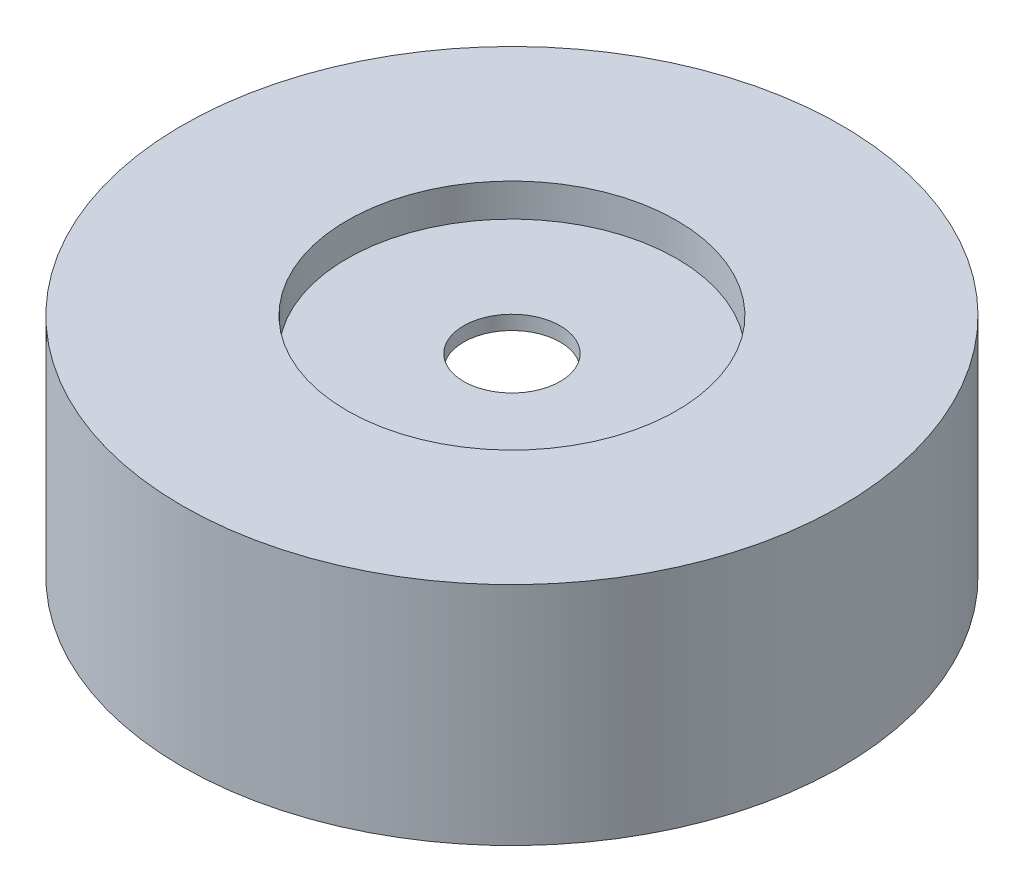
SolidWorks part; units mm, degrees
ref_plane "Front Plane" through (0, 0, 0) normal (0, 0, 1) x (1, 0, 0)
ref_plane "Top Plane" through (0, 0, 0) normal (0, 1, 0) x (1, 0, 0)
ref_plane "Right Plane" through (0, 0, 0) normal (1, 0, 0) x (0, 0, -1)
sketch "Sketch1" plane through (0, 0, 0) normal (0, 1, 0) x (1, 0, 0)
  circle A0 centre (0, 0) radius 70
  dimension "D1" = 140
extrude "Boss-Extrude1" add sketch "Sketch1" along normal blind 48
sketch "Sketch2" plane through (0, 48, 0) normal (0, 1, 0) x (1, 0, 0)
  circle A0 centre (0, 0) radius 35
  point P3 (1.6536, 0)
  point P4 (1.6536, 0)
  dimension "D1" = 70
  dimension "D2" = 0
  dimension "D3" = 0
extrude "Cut-Extrude1" cut sketch "Sketch2" against normal blind 7
sketch "Sketch3" plane through (0, 41, 0) normal (0, 1, 0) x (1, 0, 0)
  circle A0 centre (0, 0) radius 10.25
  dimension "D1" = 20.5
extrude "Cut-Extrude2" cut sketch "Sketch3" against normal through all
sketch "Sketch4" plane through (0, 0, 0) normal (0, -1, 0) x (1, 0, 0)
  circle A0 centre (0, 0) radius 65
  dimension "D1" = 130
extrude "Cut-Extrude4" cut sketch "Sketch4" against normal blind 38 contours A0
sketch "Sketch7" plane through (0, 38, 0) normal (0, -1, 0) x (1, 0, 0)
  line L0 (0, 0) -> (-50, 0)
  line L1 (-50, 0) -> (-65, 0)
  line L3 (-57.5, 4.9075) -> (-61.75, 2.4537)
  line L4 (-61.75, 2.4537) -> (-61.75, -2.4537)
  line L5 (-61.75, -2.4537) -> (-57.5, -4.9075)
  line L6 (-57.5, -4.9075) -> (-53.25, -2.4537)
  line L7 (-53.25, -2.4537) -> (-53.25, 2.4537)
  line L8 (-53.25, 2.4537) -> (-57.5, 4.9075)
  circle A0 centre (0, 0) radius 65 construction
  circle A1 centre (-57.5, 0) radius 4.25 construction
  dimension "D1" = 50
  dimension "D2" = 8.5
extrude "Boss-Extrude2" add sketch "Sketch7" along normal up to surface (38 mm away) contours L8 L3 L4 L5 L6 L7 up to face at (0, 0, -65)
sketch "Sketch10" plane through (0, 0, 0) normal (0, -1, 0) x (1, 0, 0)
  line L0 (-53.25, 0) -> (-61.75, 0) construction
  line L1 (-53.25, -2.4537) -> (-53.25, 2.4537) construction
  line L2 (-61.75, 2.4537) -> (-61.75, -2.4537) construction
  line L4 (-57.5, 3.1754) -> (-60.25, 1.5877)
  line L5 (-60.25, 1.5877) -> (-60.25, -1.5877)
  line L6 (-60.25, -1.5877) -> (-57.5, -3.1754)
  line L7 (-57.5, -3.1754) -> (-54.75, -1.5877)
  line L8 (-54.75, -1.5877) -> (-54.75, 1.5877)
  line L9 (-54.75, 1.5877) -> (-57.5, 3.1754)
  circle A0 centre (-57.5, 0) radius 2.75 construction
  dimension "D1" = 5.5
extrude "Cut-Extrude5" cut sketch "Sketch10" against normal blind 25 contours L9 L4 L5 L6 L7 L8
pattern_circular "CirPattern1" count 4 over 360 about axis through (0, 0, 0) along (0, 1, 0) of "Boss-Extrude2", "Cut-Extrude5"
sketch "Sketch12" plane through (0, 38, 0) normal (0, -1, 0) x (1, 0, 0)
  line L0 (0, 0) -> (45.9619, -45.9619) construction
  line L1 (0, 0) -> (-45.9619, 45.9619) construction
  line L2 (0, 0) -> (-45.9619, -45.9619) construction
  line L3 (0, 0) -> (45.9619, 45.9619) construction
  circle A0 centre (0, 0) radius 65 construction
  circle A1 centre (0, 0) radius 65 construction
sketch "Sketch14" plane through (0, 38, 0) normal (0, -1, 0) x (1, 0, 0)
  line L0 (0, 0) -> (-45.9619, 45.9619) construction
  line L2 (0, 0) -> (45.9619, 45.9619) construction
  line L3 (25.2678, 38.8909) -> (26.4225, 36.8909)
  line L4 (26.4225, 36.8909) -> (28.7319, 36.8909)
  line L5 (28.7319, 36.8909) -> (29.8866, 38.8909)
  line L6 (29.8866, 38.8909) -> (28.7319, 40.8909)
  line L7 (28.7319, 40.8909) -> (26.4225, 40.8909)
  line L8 (26.4225, 40.8909) -> (25.2678, 38.8909)
  line L10 (31.0413, 38.8909) -> (29.3092, 41.8909)
  line L11 (29.3092, 41.8909) -> (25.8451, 41.8909)
  line L12 (25.8451, 41.8909) -> (24.1131, 38.8909)
  line L13 (24.1131, 38.8909) -> (25.8451, 35.8909)
  line L14 (25.8451, 35.8909) -> (29.3092, 35.8909)
  line L15 (29.3092, 35.8909) -> (31.0413, 38.8909)
  circle A1 centre (27.5772, 38.8909) radius 2 construction
  circle A2 centre (27.5772, 38.8909) radius 3 construction
  point P14 (27.5772, 35.8909)
  point P21 (0, 0)
  dimension "D1" = 8
  dimension "D2" = 47
  dimension "D4" = 4
  dimension "D5" = 1
extrude "Boss-Extrude3" add sketch "Sketch14" along normal blind 3
ref_plane "Plane1" through (0, 0, 0) normal (-0.7071, 0, 0.7071) x (0.7071, 0, 0.7071)
mirror "Mirror1" about plane through (0, 0, 0) normal (-0.7071, 0, 0.7071) of "Boss-Extrude3"
